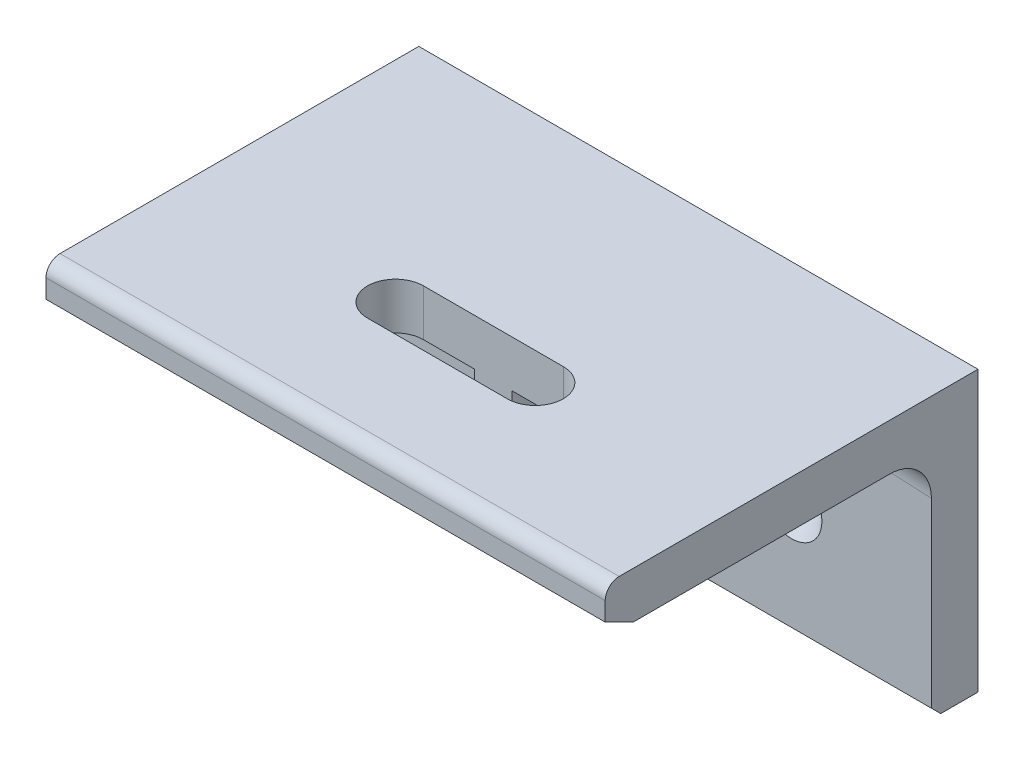
SolidWorks part; units mm, degrees
ref_plane "前视基准面" through (0, 0, 0) normal (0, 0, 1) x (1, 0, 0)
ref_plane "上视基准面" through (0, 0, 0) normal (0, 1, 0) x (1, 0, 0)
ref_plane "右视基准面" through (0, 0, 0) normal (1, 0, 0) x (0, 0, -1)
ref_plane "基准面1" through (0, 50, 0) normal (0, 1, 0) x (1, 0, 0)
ref_plane "基准面2" through (56, 0, 0) normal (1, 0, 0) x (0, 0, -1)
ref_plane "基准面3" through (120, 0, 0) normal (1, 0, 0) x (0, 0, -1)
sketch "草图8" plane through (0, 0, 0) normal (1, 0, 0) x (0, 0, -1)
  line L0 (0, 0) -> (0, 60)
  line L1 (0, 60) -> (-80, 60)
  line L2 (-80, 60) -> (-80, 50)
  line L3 (-80, 50) -> (-10, 50)
  line L4 (-10, 50) -> (-10, 0)
  line L5 (-10, 0) -> (0, 0)
extrude "凸台-拉伸6" add sketch "草图8" along normal blind 120
sketch "草图9" plane through (0, 0, 0) normal (1, 0, 0) x (0, 0, -1)
  line L0 (-13, 50) -> (-10, 50)
  line L1 (-10, 50) -> (-10, 47)
  arc A0 (-10, 47) -> (-13, 50) centre (-13, 47) ccw
sketch "草图10" plane through (120, 0, 0) normal (1, 0, 0) x (0, 0, -1)
  line L0 (-19, 50) -> (-10, 50)
  line L1 (-10, 50) -> (-10, 41)
  arc A0 (-10, 41) -> (-19, 50) centre (-19, 41) ccw
loft "放样2" add profiles "草图9", "草图10"
sketch "草图11" plane through (56, 0, 0) normal (1, 0, 0) x (0, 0, -1)
  line L0 (-10, 50) -> (-10, 10)
  line L1 (-10, 10) -> (-60, 50)
  line L2 (-60, 50) -> (-10, 50)
extrude "凸台-拉伸7" add sketch "草图11" along normal blind 8
sketch "草图13" plane through (0, 0, 0) normal (1, 0, 0) x (0, 0, -1)
  line L0 (-80, 50) -> (-74, 50)
  line L1 (-74, 50) -> (-80, 53)
  line L2 (-80, 53) -> (-80, 50)
extrude "切除-拉伸3" cut sketch "草图13" along normal blind 120
fillet "圆角2" radius 3 1 edges at (60, 60, 80)
chamfer "倒角1" distance 2 angle 45 1 edges at (60, 0, 10)
ref_plane "基准面4" through (0, 0, 10) normal (0, 0, 1) x (1, 0, 0)
sketch "草图14" plane through (0, 0, 10) normal (0, 0, 1) x (1, 0, 0)
  circle A0 centre (30, 25) radius 6.5
  circle A1 centre (90, 25) radius 6.5
extrude "切除-拉伸4" cut sketch "草图14" against normal blind 3.2 draft 45
sketch "草图15" plane through (0, 0, 10) normal (0, 0, 1) x (1, 0, 0)
  circle A0 centre (30, 25) radius 3.3
  circle A1 centre (90, 25) radius 3.3
extrude "切除-拉伸5" cut sketch "草图15" against normal through all
ref_plane "基准面5" through (0, 60, 0) normal (0, 1, 0) x (1, 0, 0)
sketch "草图16" plane through (0, 60, 0) normal (0, 1, 0) x (1, 0, 0)
  line L0 (45, -44) -> (75, -44)
  line L1 (75, -56) -> (45, -56)
  arc A0 (75, -44) -> (75, -56) centre (75, -50) cw
  arc A1 (45, -56) -> (45, -44) centre (45, -50) cw
extrude "切除-拉伸6" cut sketch "草图16" against normal through all
